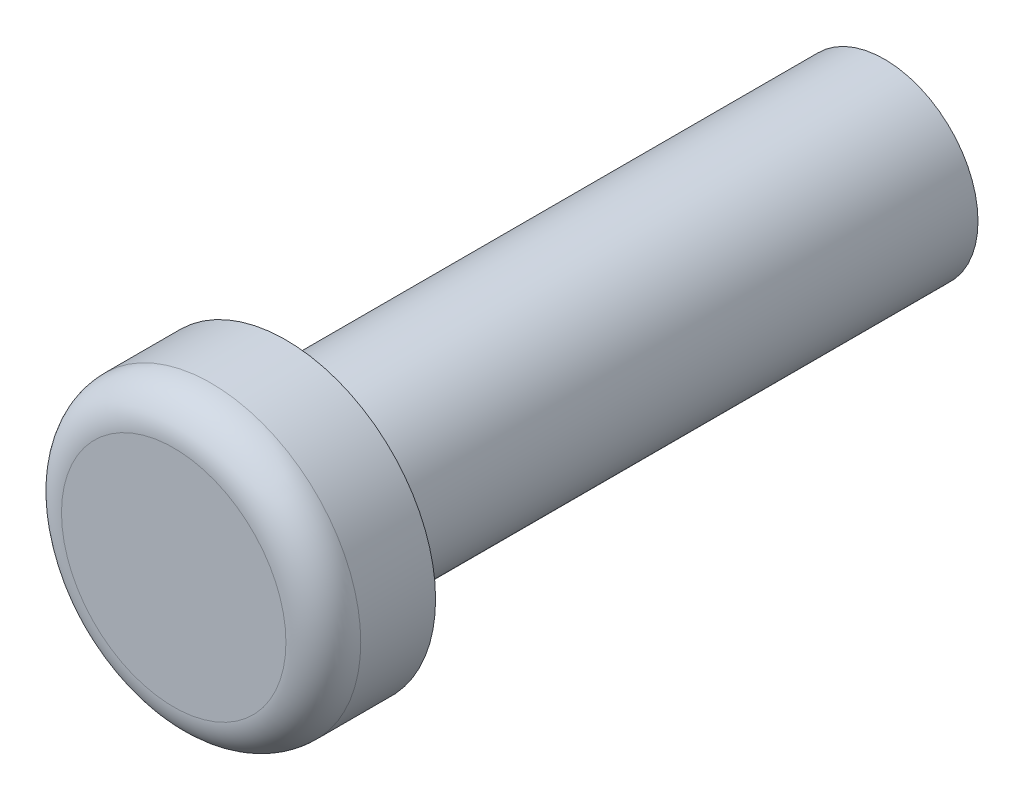
SolidWorks part; units mm, degrees
ref_plane "Front Plane" through (0, 0, 0) normal (0, 0, 1) x (1, 0, 0)
ref_plane "Top Plane" through (0, 0, 0) normal (0, 1, 0) x (1, 0, 0)
ref_plane "Right Plane" through (0, 0, 0) normal (1, 0, 0) x (0, 0, -1)
sketch "Sketch1" plane through (0, 0, 0) normal (0, 0, 1) x (1, 0, 0)
  circle A0 centre (-20, -30) radius 2.5
  point P3 (0, 0)
  dimension "D1" = 5
extrude "Boss-Extrude1" add sketch "Sketch1" against normal blind 16
sketch "Sketch2" plane through (0, 0, 0) normal (0, 0, 1) x (1, 0, 0)
  circle A0 centre (-20, -30) radius 4
  dimension "D1" = 8
extrude "Boss-Extrude2" add sketch "Sketch2" along normal blind 3
fillet "Fillet1" radius 1 1 edges at (-16, -30, 3)
